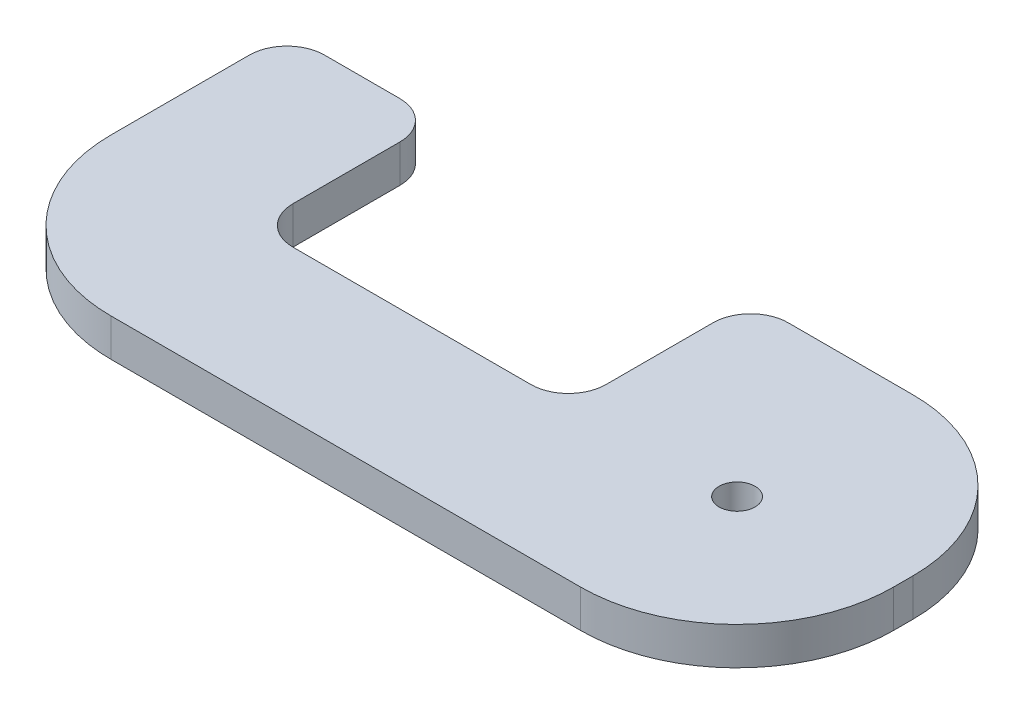
SolidWorks part; units mm, degrees
ref_plane "Front Plane" through (0, 0, 0) normal (0, 0, 1) x (1, 0, 0)
ref_plane "Top Plane" through (0, 0, 0) normal (0, 1, 0) x (1, 0, 0)
ref_plane "Right Plane" through (0, 0, 0) normal (1, 0, 0) x (0, 0, -1)
sketch "Sketch1" plane through (0, 0, 0) normal (0, 1, 0) x (1, 0, 0)
  line L1 (-25.4, 10.795) -> (25.4, 10.795)
  line L2 (-25.4, 10.795) -> (-25.4, -10.795)
  line L3 (-25.4, -10.795) -> (25.4, -10.795)
  line L4 (25.4, 10.795) -> (25.4, -10.795)
  dimension "D1" = 21.59
  dimension "D2" = 50.8
  dimension "D3" = 10.795
  dimension "D4" = 25.4
extrude "Boss-Extrude1" add sketch "Sketch1" along normal blind 3.175
fillet "Fillet1" radius 10.16 2 edges at (-25.4, 1.5875, 10.795) (25.4, 1.5875, 10.795)
sketch "Sketch3" plane through (0, 3.175, 0) normal (0, 1, 0) x (1, 0, 0)
  line L0 (-7.7526, -0.635) -> (18.5521, -0.635) construction
  circle A0 centre (15.24, -0.635) radius 1.1671
  arc A2 (15.24, -10.795) -> (25.4, -0.635) centre (15.24, -0.635) ccw construction
  circle A3 centre (-3.81, -0.635) radius 1.1671
  dimension "D1" = 2.3343
  dimension "D6" = 2.3343
  dimension "D5" = 19.05
extrude "Cut-Extrude1" cut sketch "Sketch3" against normal through all contours A0
fillet "Fillet3" radius 10.16 1 edges at (25.4, 1.5875, -10.795)
scale "Scale1" scale about centroid uniform scaling no x scale factor 1.3 y scale factor 1 z scale factor 1.3
sketch "Sketch4" plane through (0, 3.175, 0) normal (0, 1, 0) x (1, 0, 0)
  line L0 (19.9809, 13.9775) -> (-32.8511, 13.9775) construction
  line L1 (6.2649, 13.9775) -> (-20.1511, 13.9775)
  line L2 (6.2649, 13.9775) -> (6.2649, -1.3895)
  line L3 (6.2649, -1.3895) -> (-20.1511, -1.3895)
  line L4 (-20.1511, 13.9775) -> (-20.1511, -1.3895)
  line L5 (-19.6431, -14.0895) -> (19.9809, -14.0895) construction
  line L6 (-32.8511, 13.9775) -> (-32.8511, -0.8815) construction
  line L7 (33.1889, -0.8815) -> (33.1889, 0.7695) construction
  dimension "D1" = 12.7
  dimension "D2" = 12.7
  dimension "D3" = 26.924
extrude "Cut-Extrude2" cut sketch "Sketch4" against normal through all
fillet "Fillet4" radius 3.175 5 edges at (-20.1511, 1.5875, 1.3895) (6.2649, 1.5875, 1.3895) (6.2649, 1.5875, -13.9775) (-20.1511, 1.5875, -13.9775) (-32.8511, 1.5875, -13.9775)
equation "\"D4@Sketch1\"=\"D2@Sketch1\"/2"
equation "\"D3@Sketch1\"=\"D1@Sketch1\"/2"
